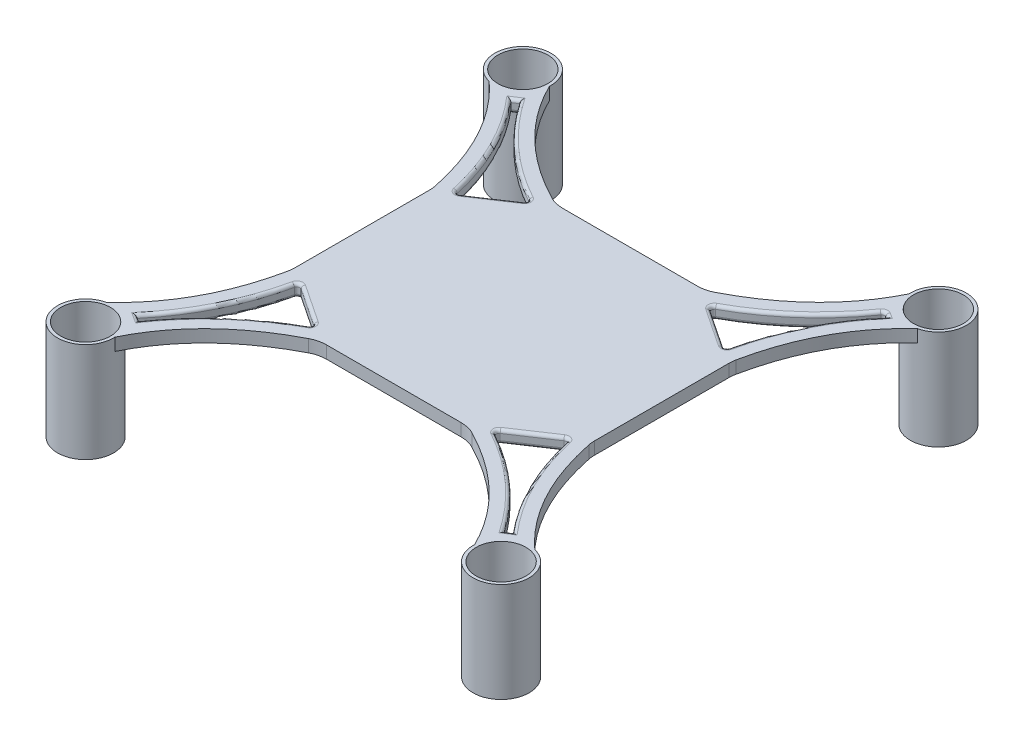
SolidWorks part; units mm, degrees
ref_plane "Front Plane" through (0, 0, 0) normal (0, 0, 1) x (1, 0, 0)
ref_plane "Top Plane" through (0, 0, 0) normal (0, 1, 0) x (1, 0, 0)
ref_plane "Right Plane" through (0, 0, 0) normal (1, 0, 0) x (0, 0, -1)
sketch "Sketch1" plane through (0, 0, 0) normal (0, 1, 0) x (1, 0, 0)
  line L0 (0, 48.6138) -> (0, -54.4719) construction
  line L1 (-10.8164, 24.6879) -> (10.8164, 24.6879)
  line L2 (46.7137, 5.7094) -> (-47.0237, 5.7094) construction
  line L3 (24.068, 16.5258) -> (24.068, -5.1069)
  line L4 (-10.8164, -13.269) -> (10.8164, -13.269)
  line L5 (-24.068, 16.5258) -> (-24.068, -5.1069)
  circle A0 centre (33.37, 40.8271) radius 4
  arc A1 (13.1162, 25.2482) -> (10.8164, 24.6879) centre (10.8164, 29.6879) cw
  arc A2 (24.1737, 17.5483) -> (24.068, 16.5258) centre (29.068, 16.5258) ccw
  arc A3 (24.1737, -6.1295) -> (24.068, -5.1069) centre (29.068, -5.1069) cw
  circle A4 centre (33.37, -29.4083) radius 4
  arc A5 (13.1162, -13.8293) -> (10.8164, -13.269) centre (10.8164, -18.269) ccw
  arc A6 (-13.1162, 25.2482) -> (-10.8164, 24.6879) centre (-10.8164, 29.6879) ccw
  arc A7 (-13.1162, -13.8293) -> (-10.8164, -13.269) centre (-10.8164, -18.269) cw
  circle A8 centre (-33.37, -29.4083) radius 4
  circle A9 centre (-33.37, 40.8271) radius 4
  arc A10 (-24.1737, 17.5483) -> (-24.068, 16.5258) centre (-29.068, 16.5258) cw
  arc A11 (-24.1737, -6.1295) -> (-24.068, -5.1069) centre (-29.068, -5.1069) ccw
  spline S0 degree 3 poles (13.1162, 25.2482) (17.1244, 27.3245) (23.8928, 32.2537) (28.1654, 38.7361) (29.6777, 42.3656) knots 0.037225 0.037225 0.037225 0.037225 0.443973 0.850721 0.850721 0.850721 0.850721
  spline S1 degree 3 poles (24.1737, 17.5483) (25.0548, 21.7657) (27.8837, 29.4488) (32.8158, 35.2456) (35.8785, 37.7115) knots 0.053222 0.053222 0.053222 0.053222 0.443973 0.850721 0.850721 0.850721 0.850721
  spline S2 degree 3 poles (24.1737, -6.1295) (25.0548, -10.3468) (27.8837, -18.0299) (32.8158, -23.8267) (35.8785, -26.2926) knots 0.053222 0.053222 0.053222 0.053222 0.443973 0.850721 0.850721 0.850721 0.850721
  spline S3 degree 3 poles (13.1162, -13.8293) (17.1244, -15.9056) (23.8928, -20.8348) (28.1654, -27.3172) (29.6777, -30.9467) knots 0.037225 0.037225 0.037225 0.037225 0.443973 0.850721 0.850721 0.850721 0.850721
  spline S4 degree 3 poles (-13.1162, -13.8293) (-17.1244, -15.9056) (-23.8928, -20.8348) (-28.1654, -27.3172) (-29.6777, -30.9467) knots 0.037225 0.037225 0.037225 0.037225 0.443973 0.850721 0.850721 0.850721 0.850721
  spline S5 degree 3 poles (-24.1737, -6.1295) (-25.0548, -10.3468) (-27.8837, -18.0299) (-32.8158, -23.8267) (-35.8785, -26.2926) knots 0.053222 0.053222 0.053222 0.053222 0.443973 0.850721 0.850721 0.850721 0.850721
  spline S6 degree 3 poles (-24.1737, 17.5483) (-25.0548, 21.7657) (-27.8837, 29.4488) (-32.8158, 35.2456) (-35.8785, 37.7115) knots 0.053222 0.053222 0.053222 0.053222 0.443973 0.850721 0.850721 0.850721 0.850721
  spline S7 degree 3 poles (-13.1162, 25.2482) (-17.1244, 27.3245) (-23.8928, 32.2537) (-28.1654, 38.7361) (-29.6777, 42.3656) knots 0.037225 0.037225 0.037225 0.037225 0.443973 0.850721 0.850721 0.850721 0.850721
  point P19 (24.068, 5.7094)
  point P37 (0, -13.269)
  point P54 (0, 24.6879)
  point P56 (0, 24.6879)
  dimension "D2" = 5
  dimension "D1" = 5
extrude "Boss-Extrude3" add sketch "Sketch1" along normal blind 2 contours A6 S7 A9 S6 A10 L5 A11 S5 A8 S4 A7 L4 A5 S3 A4 S2 A3 L3 A2 S1 A0 S0 A1 L1 | A4 | A8
sketch "Sketch5" plane through (0, 2, 0) normal (0, 1, 0) x (1, 0, 0)
  line L8 (30.1977, 35.734) -> (29.3225, 36.2906)
  line L9 (14.2661, 23.0284) -> (21.7265, 18.0596)
  line L10 (0, 31.6796) -> (0, -34.2074) construction
  line L11 (-56.7161, 5.7094) -> (61.3158, 5.7094) construction
  line L12 (-21.568, 16.5258) -> (-21.568, -5.1069)
  line L13 (-10.8164, -10.769) -> (10.8164, -10.769)
  line L14 (21.568, -5.1069) -> (21.568, 16.5258)
  line L15 (10.8164, 22.1879) -> (-10.8164, 22.1879)
  line L16 (-21.568, 16.5258) -> (-21.568, -5.1069)
  line L17 (-10.8164, -10.769) -> (10.8164, -10.769)
  line L18 (21.568, -5.1069) -> (21.568, 16.5258)
  line L19 (10.8164, 22.1879) -> (-10.8164, 22.1879)
  line L20 (-30.1977, 35.734) -> (-29.3225, 36.2906)
  line L21 (-14.2661, 23.0284) -> (-21.7265, 18.0596)
  line L22 (30.1977, -24.3151) -> (29.3225, -24.8718)
  line L23 (14.2661, -11.6095) -> (21.7265, -6.6407)
  line L24 (-14.2661, -11.6095) -> (-21.7265, -6.6407)
  line L25 (-30.1977, -24.3151) -> (-29.3225, -24.8718)
  arc A24 (21.7265, 18.0596) -> (30.1977, 35.734) centre (59.9069, 10.6274) cw
  arc A25 (14.2661, 23.0284) -> (29.3225, 36.2906) centre (-4.8209, 59.8754) ccw
  arc A26 (-14.2661, 23.0284) -> (-29.3225, 36.2906) centre (4.8209, 59.8754) cw
  arc A27 (-21.7265, 18.0596) -> (-30.1977, 35.734) centre (-59.9069, 10.6274) ccw
  arc A28 (21.7265, -6.6407) -> (30.1977, -24.3151) centre (59.9069, 0.7914) ccw
  arc A29 (14.2661, -11.6095) -> (29.3225, -24.8718) centre (-4.8209, -48.4565) cw
  arc A30 (-21.7265, -6.6407) -> (-30.1977, -24.3151) centre (-59.9069, 0.7914) cw
  arc A31 (-14.2661, -11.6095) -> (-29.3225, -24.8718) centre (4.8209, -48.4565) ccw
  arc A36 (-14.2661, 23.0284) -> (-10.8164, 22.1879) centre (-10.8164, 29.6879) ccw
  arc A37 (-31.9854, 41.404) -> (-34.3107, 39.6587) centre (-33.37, 40.8271) ccw
  arc A38 (-21.568, 16.5258) -> (-21.7265, 18.0596) centre (-29.068, 16.5258) ccw
  arc A39 (-21.7265, -6.6407) -> (-21.568, -5.1069) centre (-29.068, -5.1069) ccw
  arc A40 (-34.3107, -28.2399) -> (-31.9854, -29.9852) centre (-33.37, -29.4083) ccw
  arc A41 (-10.8164, -10.769) -> (-14.2661, -11.6095) centre (-10.8164, -18.269) ccw
  arc A42 (14.2661, -11.6095) -> (10.8164, -10.769) centre (10.8164, -18.269) ccw
  arc A43 (31.9854, -29.9852) -> (34.3107, -28.2399) centre (33.37, -29.4083) ccw
  arc A44 (21.568, -5.1069) -> (21.7265, -6.6407) centre (29.068, -5.1069) ccw
  arc A45 (21.7265, 18.0596) -> (21.568, 16.5258) centre (29.068, 16.5258) ccw
  arc A46 (34.3107, 39.6587) -> (31.9854, 41.404) centre (33.37, 40.8271) ccw
  arc A47 (10.8164, 22.1879) -> (14.2661, 23.0284) centre (10.8164, 29.6879) ccw
  arc A48 (-14.2661, 23.0284) -> (-10.8164, 22.1879) centre (-10.8164, 29.6879) ccw
  arc A49 (-31.9854, 41.404) -> (-34.3107, 39.6587) centre (-33.37, 40.8271) ccw
  arc A50 (-21.568, 16.5258) -> (-21.7265, 18.0596) centre (-29.068, 16.5258) ccw
  arc A51 (-21.7265, -6.6407) -> (-21.568, -5.1069) centre (-29.068, -5.1069) ccw
  arc A52 (-34.3107, -28.2399) -> (-31.9854, -29.9852) centre (-33.37, -29.4083) ccw
  arc A53 (-10.8164, -10.769) -> (-14.2661, -11.6095) centre (-10.8164, -18.269) ccw
  arc A54 (14.2661, -11.6095) -> (10.8164, -10.769) centre (10.8164, -18.269) ccw
  arc A55 (31.9854, -29.9852) -> (34.3107, -28.2399) centre (33.37, -29.4083) ccw
  arc A56 (21.568, -5.1069) -> (21.7265, -6.6407) centre (29.068, -5.1069) ccw
  arc A57 (21.7265, 18.0596) -> (21.568, 16.5258) centre (29.068, 16.5258) ccw
  arc A58 (34.3107, 39.6587) -> (31.9854, 41.404) centre (33.37, 40.8271) ccw
  arc A59 (10.8164, 22.1879) -> (14.2661, 23.0284) centre (10.8164, 29.6879) ccw
  spline S24 degree 3 poles (-1293.2283, -2676.1936) (402.9954, 283.6964) (71.687, -39.0407) (-20.733, 27.0608) (-21.5941, 27.7299) (-23.2451, 29.1291) (-24.0372, 29.8607) (-26.3082, 32.1572) (-27.6818, 33.823) (-29.5062, 36.5488) (-30.0686, 37.4862) (-148.6105, 258.9601) (2211.5543, 1795.9862) (-2829.0833, -598.5842) knots -12.641044 -12.641044 -12.641044 -12.641044 0.25 0.25 0.375 0.375 0.5 0.5 0.75 0.75 0.875 0.875 29.563011 29.563011 29.563011 29.563011 only from (-14.2661, 23.0284) to (-31.9854, 41.404)
  spline S25 degree 3 poles (184.4367, 1294.6818) (-2287.7745, -1535.7828) (-189.055, 223.3772) (-29.3932, 34.7953) (-29.0569, 34.3781) (-28.4081, 33.5326) (-28.0949, 33.1036) (-27.1878, 31.798) (-26.6265, 30.9032) (-25.5858, 29.0674) (-25.1064, 28.1263) (-24.2254, 26.2004) (-23.8232, 25.2138) (14.8609, -81.4612) (-389.7731, -313.9027) (2922.9923, 517.5478) knots -28.611005 -28.611005 -28.611005 -28.611005 0.25 0.25 0.3125 0.3125 0.375 0.375 0.5 0.5 0.625 0.625 0.75 0.75 13.911662 13.911662 13.911662 13.911662 only from (-34.3107, 39.6587) to (-21.7265, 18.0596)
  spline S26 degree 3 poles (2921.1119, -516.4542) (-391.9018, 328.5971) (14.9929, 93.228) (-23.8239, -13.7968) (-24.2273, -14.786) (-25.109, -16.7127) (-25.5883, -17.6532) (-27.1475, -20.403) (-28.3481, -22.1405) (-30.0728, -24.1795) (-30.4289, -24.5805) (-31.1575, -25.3621) (-31.5307, -25.7436) (-200.6034, -190.4869) (-2092.5502, 1439.1475) (1401.2137, -2538.0416) knots -12.9551 -12.9551 -12.9551 -12.9551 0.25 0.25 0.375 0.375 0.5 0.5 0.75 0.75 0.8125 0.8125 0.875 0.875 28.469753 28.469753 28.469753 28.469753 only from (-21.7265, -6.6407) to (-34.3107, -28.2399)
  spline S27 degree 3 poles (-1299.9106, -167.3195) (2099.0764, -1746.164) (-165.6783, -228.7682) (-28.6026, -23.7794) (-28.2872, -23.3321) (-27.6386, -22.4581) (-27.3048, -22.0305) (-26.2754, -20.7747) (-25.5522, -19.9738) (-24.0357, -18.4404) (-23.2425, -17.7079) (-21.5899, -16.3076) (-20.7278, -15.6381) (71.893, 50.5892) (405.3389, -272.9519) (-1299.2596, 2684.5757) knots -27.923103 -27.923103 -27.923103 -27.923103 0.25 0.25 0.3125 0.3125 0.375 0.375 0.5 0.5 0.625 0.625 0.75 0.75 13.681261 13.681261 13.681261 13.681261 only from (-31.9854, -29.9852) to (-14.2661, -11.6095)
  spline S28 degree 3 poles (1293.2283, 2687.6124) (-402.9954, -272.2775) (-71.687, 50.4595) (20.733, -15.6419) (21.5941, -16.311) (23.2451, -17.7102) (24.0372, -18.4419) (26.3082, -20.7383) (27.6818, -22.4042) (29.5062, -25.1299) (30.0686, -26.0673) (148.6105, -247.5412) (-2211.5543, -1784.5673) (2829.0833, 610.0031) knots -12.641044 -12.641044 -12.641044 -12.641044 0.25 0.25 0.375 0.375 0.5 0.5 0.75 0.75 0.875 0.875 29.563011 29.563011 29.563011 29.563011 only from (14.2661, -11.6095) to (31.9854, -29.9852)
  spline S29 degree 3 poles (-184.4367, -1283.2629) (2287.7745, 1547.2017) (189.055, -211.9583) (29.3932, -23.3765) (29.0569, -22.9592) (28.4081, -22.1137) (28.0949, -21.6847) (27.1878, -20.3792) (26.6265, -19.4843) (25.5858, -17.6485) (25.1064, -16.7074) (24.2254, -14.7815) (23.8232, -13.7949) (-14.8609, 92.88) (389.7731, 325.3216) (-2922.9923, -506.1289) knots -28.611005 -28.611005 -28.611005 -28.611005 0.25 0.25 0.3125 0.3125 0.375 0.375 0.5 0.5 0.625 0.625 0.75 0.75 13.911662 13.911662 13.911662 13.911662 only from (34.3107, -28.2399) to (21.7265, -6.6407)
  spline S30 degree 3 poles (-2921.1119, 527.8731) (391.9018, -317.1782) (-14.9929, -81.8091) (23.8239, 25.2157) (24.2273, 26.2049) (25.109, 28.1316) (25.5883, 29.0721) (27.1475, 31.8218) (28.3481, 33.5593) (30.0728, 35.5984) (30.4289, 35.9994) (31.1575, 36.781) (31.5307, 37.1625) (200.6034, 201.9057) (2092.5502, -1427.7286) (-1401.2137, 2549.4604) knots -12.9551 -12.9551 -12.9551 -12.9551 0.25 0.25 0.375 0.375 0.5 0.5 0.75 0.75 0.8125 0.8125 0.875 0.875 28.469753 28.469753 28.469753 28.469753 only from (21.7265, 18.0596) to (34.3107, 39.6587)
  spline S31 degree 3 poles (1299.9106, 178.7384) (-2099.0764, 1757.5829) (165.6783, 240.187) (28.6026, 35.1983) (28.2872, 34.7509) (27.6386, 33.877) (27.3048, 33.4493) (26.2754, 32.1936) (25.5522, 31.3927) (24.0357, 29.8593) (23.2425, 29.1267) (21.5899, 27.7265) (20.7278, 27.0569) (-71.893, -39.1703) (-405.3389, 284.3708) (1299.2596, -2673.1568) knots -27.923103 -27.923103 -27.923103 -27.923103 0.25 0.25 0.3125 0.3125 0.375 0.375 0.5 0.5 0.625 0.625 0.75 0.75 13.681261 13.681261 13.681261 13.681261 only from (31.9854, 41.404) to (14.2661, 23.0284)
  spline S32 degree 3 poles (-14.2661, 23.0284) (-16.205, 24.0327) (-18.0703, 25.1564) (-20.733, 27.0608) (-21.5941, 27.7299) (-23.2451, 29.1291) (-24.0372, 29.8607) (-26.3082, 32.1572) (-27.6818, 33.823) (-29.5062, 36.5488) (-30.0686, 37.4862) (-31.0971, 39.4078) (-31.5644, 40.3937) (-31.9854, 41.404) knots 0 0 0 0 0.25 0.25 0.375 0.375 0.5 0.5 0.75 0.75 0.875 0.875 1 1 1 1
  spline S33 degree 3 poles (-34.3107, 39.6587) (-32.6438, 38.3167) (-31.1183, 36.8328) (-29.3932, 34.7953) (-29.0569, 34.3781) (-28.4081, 33.5326) (-28.0949, 33.1036) (-27.1878, 31.798) (-26.6265, 30.9032) (-25.5858, 29.0674) (-25.1064, 28.1263) (-24.2254, 26.2004) (-23.8232, 25.2138) (-22.7314, 22.203) (-22.1633, 20.1501) (-21.7265, 18.0596) knots 0 0 0 0 0.25 0.25 0.3125 0.3125 0.375 0.375 0.5 0.5 0.625 0.625 0.75 0.75 1 1 1 1
  spline S34 degree 3 poles (-21.7265, -6.6407) (-22.1635, -8.7325) (-22.7319, -10.786) (-23.8239, -13.7968) (-24.2273, -14.786) (-25.109, -16.7127) (-25.5883, -17.6532) (-27.1475, -20.403) (-28.3481, -22.1405) (-30.0728, -24.1795) (-30.4289, -24.5805) (-31.1575, -25.3621) (-31.5307, -25.7436) (-32.677, -26.8605) (-33.4765, -27.5682) (-34.3107, -28.2399) knots 0 0 0 0 0.25 0.25 0.375 0.375 0.5 0.5 0.75 0.75 0.8125 0.8125 0.875 0.875 1 1 1 1
  spline S35 degree 3 poles (-31.9854, -29.9852) (-31.1443, -27.9665) (-30.1197, -26.0482) (-28.6026, -23.7794) (-28.2872, -23.3321) (-27.6386, -22.4581) (-27.3048, -22.0305) (-26.2754, -20.7747) (-25.5522, -19.9738) (-24.0357, -18.4404) (-23.2425, -17.7079) (-21.5899, -16.3076) (-20.7278, -15.6381) (-18.0676, -13.7359) (-16.2038, -12.6132) (-14.2661, -11.6095) knots 0 0 0 0 0.25 0.25 0.3125 0.3125 0.375 0.375 0.5 0.5 0.625 0.625 0.75 0.75 1 1 1 1
  spline S36 degree 3 poles (14.2661, -11.6095) (16.205, -12.6139) (18.0703, -13.7375) (20.733, -15.6419) (21.5941, -16.311) (23.2451, -17.7102) (24.0372, -18.4419) (26.3082, -20.7383) (27.6818, -22.4042) (29.5062, -25.1299) (30.0686, -26.0673) (31.0971, -27.989) (31.5644, -28.9748) (31.9854, -29.9852) knots 0 0 0 0 0.25 0.25 0.375 0.375 0.5 0.5 0.75 0.75 0.875 0.875 1 1 1 1
  spline S37 degree 3 poles (34.3107, -28.2399) (32.6438, -26.8979) (31.1183, -25.414) (29.3932, -23.3765) (29.0569, -22.9592) (28.4081, -22.1137) (28.0949, -21.6847) (27.1878, -20.3792) (26.6265, -19.4843) (25.5858, -17.6485) (25.1064, -16.7074) (24.2254, -14.7815) (23.8232, -13.7949) (22.7314, -10.7842) (22.1633, -8.7312) (21.7265, -6.6407) knots 0 0 0 0 0.25 0.25 0.3125 0.3125 0.375 0.375 0.5 0.5 0.625 0.625 0.75 0.75 1 1 1 1
  spline S38 degree 3 poles (21.7265, 18.0596) (22.1635, 20.1513) (22.7319, 22.2049) (23.8239, 25.2157) (24.2273, 26.2049) (25.109, 28.1316) (25.5883, 29.0721) (27.1475, 31.8218) (28.3481, 33.5593) (30.0728, 35.5984) (30.4289, 35.9994) (31.1575, 36.781) (31.5307, 37.1625) (32.677, 38.2793) (33.4765, 38.9871) (34.3107, 39.6587) knots 0 0 0 0 0.25 0.25 0.375 0.375 0.5 0.5 0.75 0.75 0.8125 0.8125 0.875 0.875 1 1 1 1
  spline S39 degree 3 poles (31.9854, 41.404) (31.1443, 39.3854) (30.1197, 37.467) (28.6026, 35.1983) (28.2872, 34.7509) (27.6386, 33.877) (27.3048, 33.4493) (26.2754, 32.1936) (25.5522, 31.3927) (24.0357, 29.8593) (23.2425, 29.1267) (21.5899, 27.7265) (20.7278, 27.0569) (18.0676, 25.1548) (16.2038, 24.0321) (14.2661, 23.0284) knots 0 0 0 0 0.25 0.25 0.3125 0.3125 0.375 0.375 0.5 0.5 0.625 0.625 0.75 0.75 1 1 1 1
  dimension "D2" = 6
  dimension "D1" = 2.5
extrude "Cut-Extrude3" cut sketch "Sketch5" against normal blind 4 contours A27 L20 A26 L21 | A31 L25 A30 L24 | A29 L22 A28 L23 | L9 A24 L8 A25
sketch "Sketch7" plane through (0, 2, 0) normal (0, 1, 0) x (1, 0, 0)
  line L0 (0, 39.7075) -> (0, -36.8004) construction
  line L1 (24.068, 5.7094) -> (-40.5042, 5.7094) construction
  line L4 (-24.068, 16.5258) -> (-24.068, -5.1069)
  line L5 (-10.8164, -13.269) -> (10.8164, -13.269)
  line L6 (24.068, -5.1069) -> (24.068, 16.5258)
  line L7 (10.8164, 24.6879) -> (-10.8164, 24.6879)
  line L8 (-24.068, 16.5258) -> (-24.068, -5.1069)
  line L9 (-10.8164, -13.269) -> (10.8164, -13.269)
  line L10 (24.068, -5.1069) -> (24.068, 16.5258)
  line L11 (10.8164, 24.6879) -> (-10.8164, 24.6879)
  circle A0 centre (33.37, 40.8271) radius 4.5
  circle A1 centre (-33.37, 40.8271) radius 4.5
  circle A2 centre (33.37, -29.4083) radius 4.5
  circle A3 centre (-33.37, -29.4083) radius 4.5
  arc A12 (-13.1162, 25.2482) -> (-10.8164, 24.6879) centre (-10.8164, 29.6879) ccw
  arc A13 (-29.6777, 42.3656) -> (-35.8785, 37.7115) centre (-33.37, 40.8271) ccw
  arc A14 (-24.068, 16.5258) -> (-24.1737, 17.5483) centre (-29.068, 16.5258) ccw
  arc A15 (-24.1737, -6.1295) -> (-24.068, -5.1069) centre (-29.068, -5.1069) ccw
  arc A16 (-35.8785, -26.2926) -> (-29.6777, -30.9467) centre (-33.37, -29.4083) ccw
  arc A17 (-10.8164, -13.269) -> (-13.1162, -13.8293) centre (-10.8164, -18.269) ccw
  arc A18 (13.1162, -13.8293) -> (10.8164, -13.269) centre (10.8164, -18.269) ccw
  arc A19 (29.6777, -30.9467) -> (35.8785, -26.2926) centre (33.37, -29.4083) ccw
  arc A20 (24.068, -5.1069) -> (24.1737, -6.1295) centre (29.068, -5.1069) ccw
  arc A21 (24.1737, 17.5483) -> (24.068, 16.5258) centre (29.068, 16.5258) ccw
  arc A22 (35.8785, 37.7115) -> (29.6777, 42.3656) centre (33.37, 40.8271) ccw
  arc A23 (10.8164, 24.6879) -> (13.1162, 25.2482) centre (10.8164, 29.6879) ccw
  arc A24 (-13.1162, 25.2482) -> (-10.8164, 24.6879) centre (-10.8164, 29.6879) ccw
  arc A26 (-24.068, 16.5258) -> (-24.1737, 17.5483) centre (-29.068, 16.5258) ccw
  arc A27 (-24.1737, -6.1295) -> (-24.068, -5.1069) centre (-29.068, -5.1069) ccw
  arc A29 (-10.8164, -13.269) -> (-13.1162, -13.8293) centre (-10.8164, -18.269) ccw
  arc A30 (13.1162, -13.8293) -> (10.8164, -13.269) centre (10.8164, -18.269) ccw
  arc A32 (24.068, -5.1069) -> (24.1737, -6.1295) centre (29.068, -5.1069) ccw
  arc A33 (24.1737, 17.5483) -> (24.068, 16.5258) centre (29.068, 16.5258) ccw
  arc A35 (10.8164, 24.6879) -> (13.1162, 25.2482) centre (10.8164, 29.6879) ccw
  spline S8 degree 3 poles (2720.72, 1244.7307) (991.1455, 333.5721) (-865.7115, -486.6483) (635.9303, 783.1648) (2262.5906, 1965.6024) knots -14.255308 -14.255308 -14.255308 -14.255308 0.443973 15.5857 15.5857 15.5857 15.5857 only from (-13.1162, 25.2482) to (-29.6777, 42.3656)
  spline S9 degree 3 poles (-2522.8628, -1626.2016) (-933.1195, -394.5106) (705.5357, 692.6861) (-600.5192, -861.0366) (-1958.2843, -2267.0883) knots -14.68191 -14.68191 -14.68191 -14.68191 0.45997 15.158154 15.158154 15.158154 15.158154 only from (-35.8785, 37.7115) to (-24.1737, 17.5483)
  spline S10 degree 3 poles (-1958.2964, 2278.5196) (-600.523, 872.46) (705.5374, -681.2679) (-933.1178, 405.9283) (-2522.8577, 1637.6166) knots -14.254254 -14.254254 -14.254254 -14.254254 0.443973 15.585837 15.585837 15.585837 15.585837 only from (-24.1737, -6.1295) to (-35.8785, -26.2926)
  spline S11 degree 3 poles (2262.6173, -1954.203) (635.9387, -771.753) (-865.7103, 498.064) (991.1298, -322.1462) (2720.6752, -1233.2882) knots -14.697836 -14.697836 -14.697836 -14.697836 0.443973 15.143128 15.143128 15.143128 15.143128 only from (-29.6777, -30.9467) to (-13.1162, -13.8293)
  spline S12 degree 3 poles (-2720.72, -1233.3118) (-991.1455, -322.1532) (865.7115, 498.0671) (-635.9303, -771.746) (-2262.5906, -1954.1835) knots -14.255308 -14.255308 -14.255308 -14.255308 0.443973 15.5857 15.5857 15.5857 15.5857 only from (13.1162, -13.8293) to (29.6777, -30.9467)
  spline S13 degree 3 poles (2522.8628, 1637.6205) (933.1195, 405.9294) (-705.5357, -681.2672) (600.5192, 872.4554) (1958.2843, 2278.5072) knots -14.68191 -14.68191 -14.68191 -14.68191 0.45997 15.158154 15.158154 15.158154 15.158154 only from (35.8785, -26.2926) to (24.1737, -6.1295)
  spline S14 degree 3 poles (1958.2964, -2267.1008) (600.523, -861.0411) (-705.5374, 692.6868) (933.1178, -394.5094) (2522.8577, -1626.1977) knots -14.254254 -14.254254 -14.254254 -14.254254 0.443973 15.585837 15.585837 15.585837 15.585837 only from (24.1737, 17.5483) to (35.8785, 37.7115)
  spline S15 degree 3 poles (-2262.6173, 1965.6218) (-635.9387, 783.1719) (865.7103, -486.6451) (-991.1298, 333.5651) (-2720.6752, 1244.7071) knots -14.697836 -14.697836 -14.697836 -14.697836 0.443973 15.143128 15.143128 15.143128 15.143128 only from (29.6777, 42.3656) to (13.1162, 25.2482)
  spline S16 degree 3 poles (-13.1162, 25.2482) (-17.1244, 27.3245) (-23.8928, 32.2537) (-28.1654, 38.7361) (-29.6777, 42.3656) knots 0.037225 0.037225 0.037225 0.037225 0.443973 0.850721 0.850721 0.850721 0.850721
  spline S17 degree 3 poles (-35.8785, 37.7115) (-32.8158, 35.2456) (-27.8837, 29.4488) (-25.0548, 21.7657) (-24.1737, 17.5483) knots 0.053222 0.053222 0.053222 0.053222 0.45997 0.850721 0.850721 0.850721 0.850721
  spline S18 degree 3 poles (-24.1737, -6.1295) (-25.0548, -10.3468) (-27.8837, -18.0299) (-32.8158, -23.8267) (-35.8785, -26.2926) knots 0.053222 0.053222 0.053222 0.053222 0.443973 0.850721 0.850721 0.850721 0.850721
  spline S19 degree 3 poles (-29.6777, -30.9467) (-28.1654, -27.3172) (-23.8928, -20.8348) (-17.1244, -15.9056) (-13.1162, -13.8293) knots 0.037225 0.037225 0.037225 0.037225 0.443973 0.850721 0.850721 0.850721 0.850721
  spline S20 degree 3 poles (13.1162, -13.8293) (17.1244, -15.9056) (23.8928, -20.8348) (28.1654, -27.3172) (29.6777, -30.9467) knots 0.037225 0.037225 0.037225 0.037225 0.443973 0.850721 0.850721 0.850721 0.850721
  spline S21 degree 3 poles (35.8785, -26.2926) (32.8158, -23.8267) (27.8837, -18.0299) (25.0548, -10.3468) (24.1737, -6.1295) knots 0.053222 0.053222 0.053222 0.053222 0.45997 0.850721 0.850721 0.850721 0.850721
  spline S22 degree 3 poles (24.1737, 17.5483) (25.0548, 21.7657) (27.8837, 29.4488) (32.8158, 35.2456) (35.8785, 37.7115) knots 0.053222 0.053222 0.053222 0.053222 0.443973 0.850721 0.850721 0.850721 0.850721
  spline S23 degree 3 poles (29.6777, 42.3656) (28.1654, 38.7361) (23.8928, 32.2537) (17.1244, 27.3245) (13.1162, 25.2482) knots 0.037225 0.037225 0.037225 0.037225 0.443973 0.850721 0.850721 0.850721 0.850721
  dimension "D1" = 0
extrude "Cut-Extrude5" cut sketch "Sketch7" against normal blind 4 contours A0 | A2 | A3 | A1
sketch "Sketch9" plane through (0, 2, 0) normal (0, 1, 0) x (1, 0, 0)
  line L0 (0, 27.8112) -> (0, -19.6156) construction
  line L1 (-24.068, 5.7094) -> (24.068, 5.7094) construction
  line L4 (24.068, -5.1069) -> (24.068, 16.5258)
  line L5 (10.8164, 24.6879) -> (-10.8164, 24.6879)
  line L6 (-24.068, 16.5258) -> (-24.068, -5.1069)
  line L7 (-10.8164, -13.269) -> (10.8164, -13.269)
  line L8 (24.068, -5.1069) -> (24.068, 16.5258)
  line L9 (10.8164, 24.6879) -> (-10.8164, 24.6879)
  line L10 (-24.068, 16.5258) -> (-24.068, -5.1069)
  line L11 (-10.8164, -13.269) -> (10.8164, -13.269)
  circle A0 centre (33.37, 40.8271) radius 4.5
  circle A1 centre (-33.37, 40.8271) radius 4.5
  circle A2 centre (33.37, -29.4083) radius 4.5
  circle A3 centre (-33.37, -29.4083) radius 4.5
  arc A12 (34.4034, -25.0285) -> (28.8759, -29.1773) centre (33.37, -29.4083) ccw
  arc A13 (24.068, -5.1069) -> (24.1737, -6.1295) centre (29.068, -5.1069) ccw
  arc A14 (24.1737, 17.5483) -> (24.068, 16.5258) centre (29.068, 16.5258) ccw
  arc A15 (28.8759, 40.5962) -> (34.4034, 36.4474) centre (33.37, 40.8271) ccw
  arc A16 (10.8164, 24.6879) -> (13.1162, 25.2482) centre (10.8164, 29.6879) ccw
  arc A17 (-13.1162, 25.2482) -> (-10.8164, 24.6879) centre (-10.8164, 29.6879) ccw
  arc A18 (-34.4034, 36.4474) -> (-28.8759, 40.5962) centre (-33.37, 40.8271) ccw
  arc A19 (-24.068, 16.5258) -> (-24.1737, 17.5483) centre (-29.068, 16.5258) ccw
  arc A20 (-24.1737, -6.1295) -> (-24.068, -5.1069) centre (-29.068, -5.1069) ccw
  arc A21 (-28.8759, -29.1773) -> (-34.4034, -25.0285) centre (-33.37, -29.4083) ccw
  arc A22 (-10.8164, -13.269) -> (-13.1162, -13.8293) centre (-10.8164, -18.269) ccw
  arc A23 (13.1162, -13.8293) -> (10.8164, -13.269) centre (10.8164, -18.269) ccw
  arc A24 (34.4034, -25.0285) -> (28.8759, -29.1773) centre (33.37, -29.4083) ccw
  arc A25 (24.068, -5.1069) -> (24.1737, -6.1295) centre (29.068, -5.1069) ccw
  arc A26 (24.1737, 17.5483) -> (24.068, 16.5258) centre (29.068, 16.5258) ccw
  arc A27 (28.8759, 40.5962) -> (34.4034, 36.4474) centre (33.37, 40.8271) ccw
  arc A28 (10.8164, 24.6879) -> (13.1162, 25.2482) centre (10.8164, 29.6879) ccw
  arc A29 (-13.1162, 25.2482) -> (-10.8164, 24.6879) centre (-10.8164, 29.6879) ccw
  arc A30 (-34.4034, 36.4474) -> (-28.8759, 40.5962) centre (-33.37, 40.8271) ccw
  arc A31 (-24.068, 16.5258) -> (-24.1737, 17.5483) centre (-29.068, 16.5258) ccw
  arc A32 (-24.1737, -6.1295) -> (-24.068, -5.1069) centre (-29.068, -5.1069) ccw
  arc A33 (-28.8759, -29.1773) -> (-34.4034, -25.0285) centre (-33.37, -29.4083) ccw
  arc A34 (-10.8164, -13.269) -> (-13.1162, -13.8293) centre (-10.8164, -18.269) ccw
  arc A35 (13.1162, -13.8293) -> (10.8164, -13.269) centre (10.8164, -18.269) ccw
  spline S8 degree 3 poles (-2720.6991, -1233.3008) (-991.1382, -322.15) (865.6056, 498.0192) (-635.764, -771.6053) (-2262.0578, -1953.7963) knots -14.255249 -14.255249 -14.255249 -14.255249 0.443973 15.584047 15.584047 15.584047 15.584047 only from (13.1162, -13.8293) to (28.8759, -29.1773)
  spline S9 degree 3 poles (2522.2992, 1637.1839) (932.923, 405.7991) (-705.4608, -681.1763) (600.5246, 872.4619) (1958.3014, 2278.5249) knots -14.747408 -14.747408 -14.747408 -14.747408 0.392682 15.090928 15.090928 15.090928 15.090928 only from (34.4034, -25.0285) to (24.1737, -6.1295)
  spline S10 degree 3 poles (1958.2819, -2267.0858) (600.5184, -861.0357) (-705.452, 692.5868) (932.9108, -394.3721) (2522.2641, -1625.7378) knots -14.254202 -14.254202 -14.254202 -14.254202 0.443973 15.583952 15.583952 15.583952 15.583952 only from (24.1737, 17.5483) to (34.4034, 36.4474)
  spline S11 degree 3 poles (-2262.0339, 1965.1978) (-635.7565, 783.0178) (865.5972, -486.5951) (-991.1288, 333.5647) (-2720.6725, 1244.7057) knots -14.763314 -14.763314 -14.763314 -14.763314 0.376685 15.075832 15.075832 15.075832 15.075832 only from (28.8759, 40.5962) to (13.1162, 25.2482)
  spline S12 degree 3 poles (2720.6991, 1244.7197) (991.1382, 333.5688) (-865.6056, -486.6003) (635.764, 783.0242) (2262.0578, 1965.2151) knots -14.255249 -14.255249 -14.255249 -14.255249 0.443973 15.584047 15.584047 15.584047 15.584047 only from (-13.1162, 25.2482) to (-28.8759, 40.5962)
  spline S13 degree 3 poles (-2522.2992, -1625.765) (-932.923, -394.3802) (705.4608, 692.5951) (-600.5246, -861.043) (-1958.3014, -2267.106) knots -14.747408 -14.747408 -14.747408 -14.747408 0.392682 15.090928 15.090928 15.090928 15.090928 only from (-34.4034, 36.4474) to (-24.1737, 17.5483)
  spline S14 degree 3 poles (-1958.2819, 2278.5047) (-600.5184, 872.4545) (705.452, -681.1679) (-932.9108, 405.791) (-2522.2641, 1637.1567) knots -14.254202 -14.254202 -14.254202 -14.254202 0.443973 15.583952 15.583952 15.583952 15.583952 only from (-24.1737, -6.1295) to (-34.4034, -25.0285)
  spline S15 degree 3 poles (2262.0339, -1953.7789) (635.7565, -771.599) (-865.5972, 498.0139) (991.1288, -322.1458) (2720.6725, -1233.2868) knots -14.763314 -14.763314 -14.763314 -14.763314 0.376685 15.075832 15.075832 15.075832 15.075832 only from (-28.8759, -29.1773) to (-13.1162, -13.8293)
  spline S16 degree 3 poles (13.1162, -13.8293) (17.1244, -15.9056) (23.333, -20.4271) (27.4415, -26.2554) (28.8759, -29.1773) knots 0.037225 0.037225 0.037225 0.037225 0.443973 0.783433 0.783433 0.783433 0.783433
  spline S17 degree 3 poles (34.4034, -25.0285) (31.9985, -22.8351) (27.645, -17.3817) (25.0548, -10.3468) (24.1737, -6.1295) knots 0.053222 0.053222 0.053222 0.053222 0.392682 0.783433 0.783433 0.783433 0.783433
  spline S18 degree 3 poles (24.1737, 17.5483) (25.0548, 21.7657) (27.645, 28.8006) (31.9985, 34.254) (34.4034, 36.4474) knots 0.053222 0.053222 0.053222 0.053222 0.443973 0.783433 0.783433 0.783433 0.783433
  spline S19 degree 3 poles (28.8759, 40.5962) (27.4415, 37.6743) (23.333, 31.8459) (17.1244, 27.3245) (13.1162, 25.2482) knots 0.037225 0.037225 0.037225 0.037225 0.376685 0.783433 0.783433 0.783433 0.783433
  spline S20 degree 3 poles (-13.1162, 25.2482) (-17.1244, 27.3245) (-23.333, 31.8459) (-27.4415, 37.6743) (-28.8759, 40.5962) knots 0.037225 0.037225 0.037225 0.037225 0.443973 0.783433 0.783433 0.783433 0.783433
  spline S21 degree 3 poles (-34.4034, 36.4474) (-31.9985, 34.254) (-27.645, 28.8006) (-25.0548, 21.7657) (-24.1737, 17.5483) knots 0.053222 0.053222 0.053222 0.053222 0.392682 0.783433 0.783433 0.783433 0.783433
  spline S22 degree 3 poles (-24.1737, -6.1295) (-25.0548, -10.3468) (-27.645, -17.3817) (-31.9985, -22.8351) (-34.4034, -25.0285) knots 0.053222 0.053222 0.053222 0.053222 0.443973 0.783433 0.783433 0.783433 0.783433
  spline S23 degree 3 poles (-28.8759, -29.1773) (-27.4415, -26.2554) (-23.333, -20.4271) (-17.1244, -15.9056) (-13.1162, -13.8293) knots 0.037225 0.037225 0.037225 0.037225 0.376685 0.783433 0.783433 0.783433 0.783433
  dimension "D1" = 0
extrude "Boss-Extrude4" add sketch "Sketch9" against normal blind 16 contours A0 | A3 | A2 | A1
sketch "Sketch10" plane through (0, 2, 0) normal (0, 1, 0) x (1, 0, 0)
  line L0 (0, 38.5683) -> (0, -35.8055) construction
  line L1 (-24.068, 5.7094) -> (24.068, 5.7094) construction
  line L4 (24.068, -5.1069) -> (24.068, 16.5258)
  line L5 (10.8164, 24.6879) -> (-10.8164, 24.6879)
  line L6 (-24.068, 16.5258) -> (-24.068, -5.1069)
  line L7 (-10.8164, -13.269) -> (10.8164, -13.269)
  line L8 (24.068, -5.1069) -> (24.068, 16.5258)
  line L9 (10.8164, 24.6879) -> (-10.8164, 24.6879)
  line L10 (-24.068, 16.5258) -> (-24.068, -5.1069)
  line L11 (-10.8164, -13.269) -> (10.8164, -13.269)
  circle A0 centre (33.37, 40.8271) radius 4
  circle A1 centre (-33.37, 40.8271) radius 4
  circle A2 centre (33.37, -29.4083) radius 4
  circle A3 centre (-33.37, -29.4083) radius 4
  arc A12 (28.8759, -29.1773) -> (34.4034, -25.0285) centre (33.37, -29.4083) ccw
  arc A13 (24.068, -5.1069) -> (24.1737, -6.1295) centre (29.068, -5.1069) ccw
  arc A14 (24.1737, 17.5483) -> (24.068, 16.5258) centre (29.068, 16.5258) ccw
  arc A15 (34.4034, 36.4474) -> (28.8759, 40.5962) centre (33.37, 40.8271) ccw
  arc A16 (10.8164, 24.6879) -> (13.1162, 25.2482) centre (10.8164, 29.6879) ccw
  arc A17 (-13.1162, 25.2482) -> (-10.8164, 24.6879) centre (-10.8164, 29.6879) ccw
  arc A18 (-28.8759, 40.5962) -> (-34.4034, 36.4474) centre (-33.37, 40.8271) ccw
  arc A19 (-24.068, 16.5258) -> (-24.1737, 17.5483) centre (-29.068, 16.5258) ccw
  arc A20 (-24.1737, -6.1295) -> (-24.068, -5.1069) centre (-29.068, -5.1069) ccw
  arc A21 (-34.4034, -25.0285) -> (-28.8759, -29.1773) centre (-33.37, -29.4083) ccw
  arc A22 (-10.8164, -13.269) -> (-13.1162, -13.8293) centre (-10.8164, -18.269) ccw
  arc A23 (13.1162, -13.8293) -> (10.8164, -13.269) centre (10.8164, -18.269) ccw
  arc A24 (28.8759, -29.1773) -> (34.4034, -25.0285) centre (33.37, -29.4083) ccw
  arc A25 (24.068, -5.1069) -> (24.1737, -6.1295) centre (29.068, -5.1069) ccw
  arc A26 (24.1737, 17.5483) -> (24.068, 16.5258) centre (29.068, 16.5258) ccw
  arc A27 (34.4034, 36.4474) -> (28.8759, 40.5962) centre (33.37, 40.8271) ccw
  arc A28 (10.8164, 24.6879) -> (13.1162, 25.2482) centre (10.8164, 29.6879) ccw
  arc A29 (-13.1162, 25.2482) -> (-10.8164, 24.6879) centre (-10.8164, 29.6879) ccw
  arc A30 (-28.8759, 40.5962) -> (-34.4034, 36.4474) centre (-33.37, 40.8271) ccw
  arc A31 (-24.068, 16.5258) -> (-24.1737, 17.5483) centre (-29.068, 16.5258) ccw
  arc A32 (-24.1737, -6.1295) -> (-24.068, -5.1069) centre (-29.068, -5.1069) ccw
  arc A33 (-34.4034, -25.0285) -> (-28.8759, -29.1773) centre (-33.37, -29.4083) ccw
  arc A34 (-10.8164, -13.269) -> (-13.1162, -13.8293) centre (-10.8164, -18.269) ccw
  arc A35 (13.1162, -13.8293) -> (10.8164, -13.269) centre (10.8164, -18.269) ccw
  spline S8 degree 3 poles (-2720.6991, -1233.3008) (-991.1382, -322.15) (865.6056, 498.0192) (-635.764, -771.6053) (-2262.0578, -1953.7963) knots -14.255249 -14.255249 -14.255249 -14.255249 0.443973 15.584047 15.584047 15.584047 15.584047 only from (13.1162, -13.8293) to (28.8759, -29.1773)
  spline S9 degree 3 poles (2522.2992, 1637.1839) (932.923, 405.7991) (-705.4608, -681.1763) (600.5246, 872.4619) (1958.3014, 2278.5249) knots -14.747408 -14.747408 -14.747408 -14.747408 0.392682 15.090928 15.090928 15.090928 15.090928 only from (34.4034, -25.0285) to (24.1737, -6.1295)
  spline S10 degree 3 poles (1958.2819, -2267.0858) (600.5184, -861.0357) (-705.452, 692.5868) (932.9108, -394.3721) (2522.2641, -1625.7378) knots -14.254202 -14.254202 -14.254202 -14.254202 0.443973 15.583952 15.583952 15.583952 15.583952 only from (24.1737, 17.5483) to (34.4034, 36.4474)
  spline S11 degree 3 poles (-2262.0339, 1965.1978) (-635.7565, 783.0178) (865.5972, -486.5951) (-991.1288, 333.5647) (-2720.6725, 1244.7057) knots -14.763314 -14.763314 -14.763314 -14.763314 0.376685 15.075832 15.075832 15.075832 15.075832 only from (28.8759, 40.5962) to (13.1162, 25.2482)
  spline S12 degree 3 poles (2720.6991, 1244.7197) (991.1382, 333.5688) (-865.6056, -486.6003) (635.764, 783.0242) (2262.0578, 1965.2151) knots -14.255249 -14.255249 -14.255249 -14.255249 0.443973 15.584047 15.584047 15.584047 15.584047 only from (-13.1162, 25.2482) to (-28.8759, 40.5962)
  spline S13 degree 3 poles (-2522.2992, -1625.765) (-932.923, -394.3802) (705.4608, 692.5951) (-600.5246, -861.043) (-1958.3014, -2267.106) knots -14.747408 -14.747408 -14.747408 -14.747408 0.392682 15.090928 15.090928 15.090928 15.090928 only from (-34.4034, 36.4474) to (-24.1737, 17.5483)
  spline S14 degree 3 poles (-1958.2819, 2278.5047) (-600.5184, 872.4545) (705.452, -681.1679) (-932.9108, 405.791) (-2522.2641, 1637.1567) knots -14.254202 -14.254202 -14.254202 -14.254202 0.443973 15.583952 15.583952 15.583952 15.583952 only from (-24.1737, -6.1295) to (-34.4034, -25.0285)
  spline S15 degree 3 poles (2262.0339, -1953.7789) (635.7565, -771.599) (-865.5972, 498.0139) (991.1288, -322.1458) (2720.6725, -1233.2868) knots -14.763314 -14.763314 -14.763314 -14.763314 0.376685 15.075832 15.075832 15.075832 15.075832 only from (-28.8759, -29.1773) to (-13.1162, -13.8293)
  spline S16 degree 3 poles (13.1162, -13.8293) (17.1244, -15.9056) (23.333, -20.4271) (27.4415, -26.2554) (28.8759, -29.1773) knots 0.037225 0.037225 0.037225 0.037225 0.443973 0.783433 0.783433 0.783433 0.783433
  spline S17 degree 3 poles (34.4034, -25.0285) (31.9985, -22.8351) (27.645, -17.3817) (25.0548, -10.3468) (24.1737, -6.1295) knots 0.053222 0.053222 0.053222 0.053222 0.392682 0.783433 0.783433 0.783433 0.783433
  spline S18 degree 3 poles (24.1737, 17.5483) (25.0548, 21.7657) (27.645, 28.8006) (31.9985, 34.254) (34.4034, 36.4474) knots 0.053222 0.053222 0.053222 0.053222 0.443973 0.783433 0.783433 0.783433 0.783433
  spline S19 degree 3 poles (28.8759, 40.5962) (27.4415, 37.6743) (23.333, 31.8459) (17.1244, 27.3245) (13.1162, 25.2482) knots 0.037225 0.037225 0.037225 0.037225 0.376685 0.783433 0.783433 0.783433 0.783433
  spline S20 degree 3 poles (-13.1162, 25.2482) (-17.1244, 27.3245) (-23.333, 31.8459) (-27.4415, 37.6743) (-28.8759, 40.5962) knots 0.037225 0.037225 0.037225 0.037225 0.443973 0.783433 0.783433 0.783433 0.783433
  spline S21 degree 3 poles (-34.4034, 36.4474) (-31.9985, 34.254) (-27.645, 28.8006) (-25.0548, 21.7657) (-24.1737, 17.5483) knots 0.053222 0.053222 0.053222 0.053222 0.392682 0.783433 0.783433 0.783433 0.783433
  spline S22 degree 3 poles (-24.1737, -6.1295) (-25.0548, -10.3468) (-27.645, -17.3817) (-31.9985, -22.8351) (-34.4034, -25.0285) knots 0.053222 0.053222 0.053222 0.053222 0.443973 0.783433 0.783433 0.783433 0.783433
  spline S23 degree 3 poles (-28.8759, -29.1773) (-27.4415, -26.2554) (-23.333, -20.4271) (-17.1244, -15.9056) (-13.1162, -13.8293) knots 0.037225 0.037225 0.037225 0.037225 0.376685 0.783433 0.783433 0.783433 0.783433
  dimension "D1" = 0
extrude "Cut-Extrude6" cut sketch "Sketch10" against normal blind 16 contours A0 | A2 | A3 | A1
fillet "Fillet1" radius 0.5 41 edges at (-22.6079, 0, 17.3169) (-24.8306, 0, 16.0202) (17.9963, 0, -20.544) (22.6079, 0, 17.3169) (29.3225, 1, -36.2906) (22.6079, 0, -28.7358) (14.2661, 1, -23.0284) (22.6079, 2, -28.7358) (-29.7601, 0, 24.5935) (-29.7601, 2, 24.5935) (-17.9963, 0, 9.1251) (-14.2661, 1, 11.6095) (-21.7265, 1, 6.6407) (-22.6079, 2, 17.3169) (-24.8306, 2, 16.0202) (-17.9963, 2, 9.1251) (-14.2661, 1, -23.0284) (-21.7265, 1, -18.0596) (21.7265, 1, -18.0596) (-29.7601, 0, -36.0123) (-29.7601, 2, -36.0123) (-24.8306, 0, -27.4391) (-24.8306, 2, -27.4391) (-17.9963, 0, -20.544) (-22.6079, 0, -28.7358) (-17.9963, 2, -20.544) (-22.6079, 2, -28.7358) (17.9963, 2, -20.544) (24.8306, 0, -27.4391) (24.8306, 2, -27.4391) (29.7601, 0, -36.0123) (29.7601, 2, -36.0123) (29.7601, 0, 24.5935) (29.7601, 2, 24.5935) (24.8306, 0, 16.0202) (21.7265, 1, 6.6407) (14.2661, 1, 11.6095) (22.6079, 2, 17.3169) (24.8306, 2, 16.0202) (17.9963, 0, 9.1251) (17.9963, 2, 9.1251)
